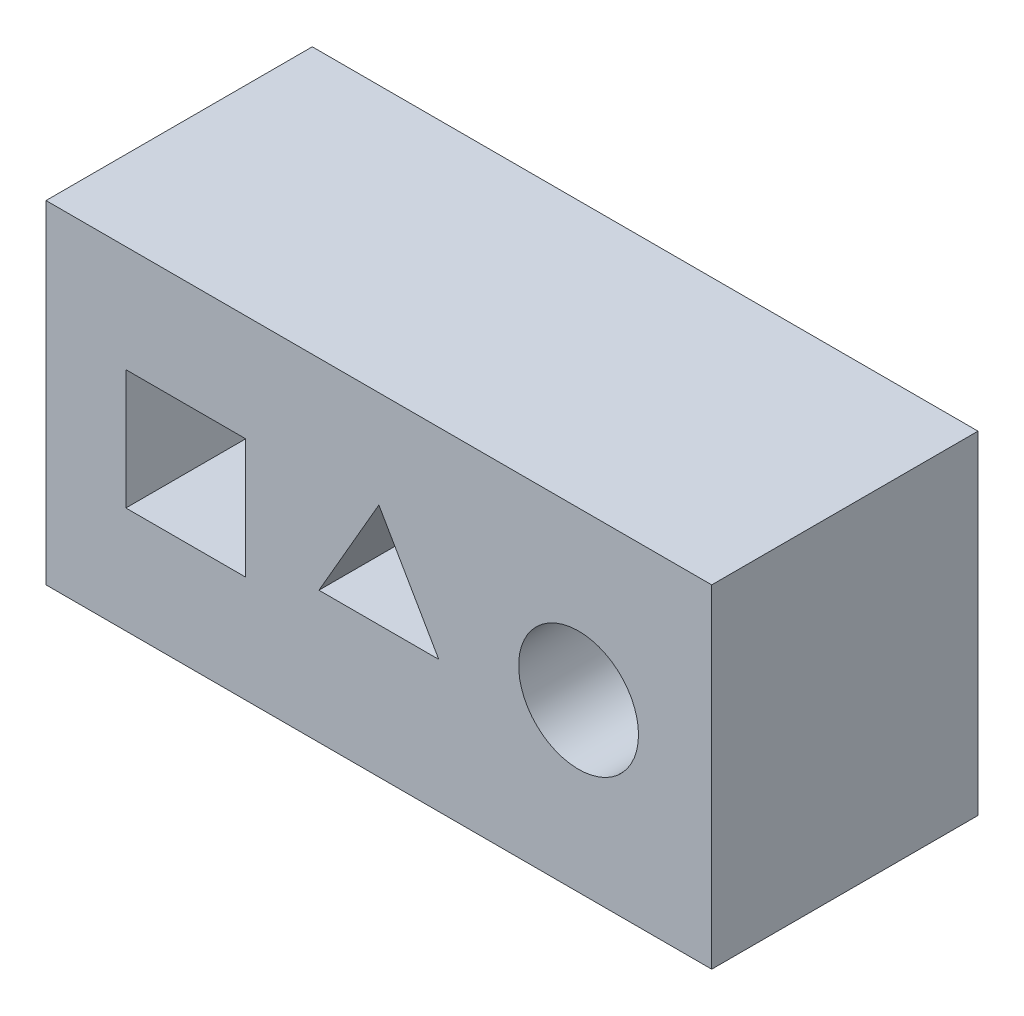
SolidWorks part; units mm, degrees
ref_plane "Front Plane" through (0, 0, 0) normal (0, 0, 1) x (1, 0, 0)
ref_plane "Top Plane" through (0, 0, 0) normal (0, 1, 0) x (1, 0, 0)
ref_plane "Right Plane" through (0, 0, 0) normal (1, 0, 0) x (0, 0, -1)
sketch "Sketch1" plane through (0, 0, 0) normal (0, 0, 1) x (1, 0, 0)
  line L1 (125, -62.5) -> (-125, -62.5)
  line L2 (125, -62.5) -> (125, 62.5)
  line L3 (125, 62.5) -> (-125, 62.5)
  line L4 (-125, -62.5) -> (-125, 62.5)
  line L5 (125, -62.5) -> (-125, 62.5) construction
  line L6 (125, 62.5) -> (-125, -62.5) construction
  line L7 (115, -57.5) -> (-115, -57.5)
  line L8 (115, -57.5) -> (115, 57.5)
  line L9 (115, 57.5) -> (-115, 57.5)
  line L10 (-115, -57.5) -> (-115, 57.5)
  line L11 (115, -57.5) -> (-115, 57.5) construction
  line L12 (115, 57.5) -> (-115, -57.5) construction
  point P0 (0, 0)
  point P6 (0, 0)
  dimension "D1" = 250
  dimension "D2" = 125
  dimension "D3" = 230
extrude "Boss-Extrude1" add sketch "Sketch1" along normal blind 100
sketch "Sketch2" plane through (0, 0, 0) normal (0, 0, -1) x (-1, 0, 0)
  line L1 (125, 62.5) -> (-125, 62.5)
  line L2 (125, 62.5) -> (125, -62.5)
  line L3 (125, -62.5) -> (-125, -62.5)
  line L4 (-125, 62.5) -> (-125, -62.5)
sketch "Sketch3" plane through (0, 0, 100) normal (0, 0, 1) x (1, 0, 0)
  line L0 (-125, 0) -> (125, 0) construction
  line L1 (-125, 62.5) -> (125, 62.5)
  line L2 (-125, 62.5) -> (-125, -62.5)
  line L3 (-125, -62.5) -> (125, -62.5)
  line L4 (125, 62.5) -> (125, -62.5)
  line L5 (0, 62.5) -> (0, -62.5) construction
  line L6 (-22.5, -12.9904) -> (0, 25.9808)
  line L7 (-95, 22.5) -> (-50, 22.5)
  line L8 (-95, 22.5) -> (-95, -22.5)
  line L9 (-95, -22.5) -> (-50, -22.5)
  line L10 (-50, 22.5) -> (-50, -22.5)
  line L11 (-95, 22.5) -> (-50, -22.5) construction
  line L12 (-95, -22.5) -> (-50, 22.5) construction
  line L14 (-1.3522, 0) -> (0, -1.3522)
  line L18 (0, 25.9808) -> (22.5, -12.9904)
  line L19 (22.5, -12.9904) -> (-22.5, -12.9904)
  line L20 (-22.5, -12.9904) -> (11.25, 6.4952) construction
  line L21 (22.5, -12.9904) -> (-11.25, 6.4952) construction
  line L22 (0, 25.9808) -> (0, 0) construction
  circle A0 centre (75, 0) radius 22.5
  point P10 (-72.5, 0)
  point P20 (0, 0)
  point P27 (7.7505, -5.3087)
  point P28 (0, 0)
  line M21 (-125, 62.5) -> (-125, -62.5)
  line M22 (-125, -62.5) -> (125, -62.5)
  line M23 (125, -62.5) -> (125, 62.5)
  line M24 (125, 62.5) -> (-125, 62.5)
  line M25 (115, -57.5) -> (-115, -57.5)
  line M26 (-115, -57.5) -> (-115, 57.5)
  line M27 (-115, 57.5) -> (115, 57.5)
  line M28 (115, 57.5) -> (115, -57.5)
  dimension "D2" = 50
  dimension "cylinder" = 45
  dimension "D1" = 30
  dimension "square2" = 45
  dimension "square" = 45
  dimension "triangle3" = 45
  dimension "triangle2" = 45
  dimension "triangle" = 45
extrude "Boss-Extrude4" add sketch "Sketch3" against normal up to surface (100 mm away) contours A0 L7 L10 L9 L8 L18 L19 L6 M25 M28 M27 M26 | M24 M21 M22 M23 M28 M25 M26 M27 up to face at (0, 0, 0)
